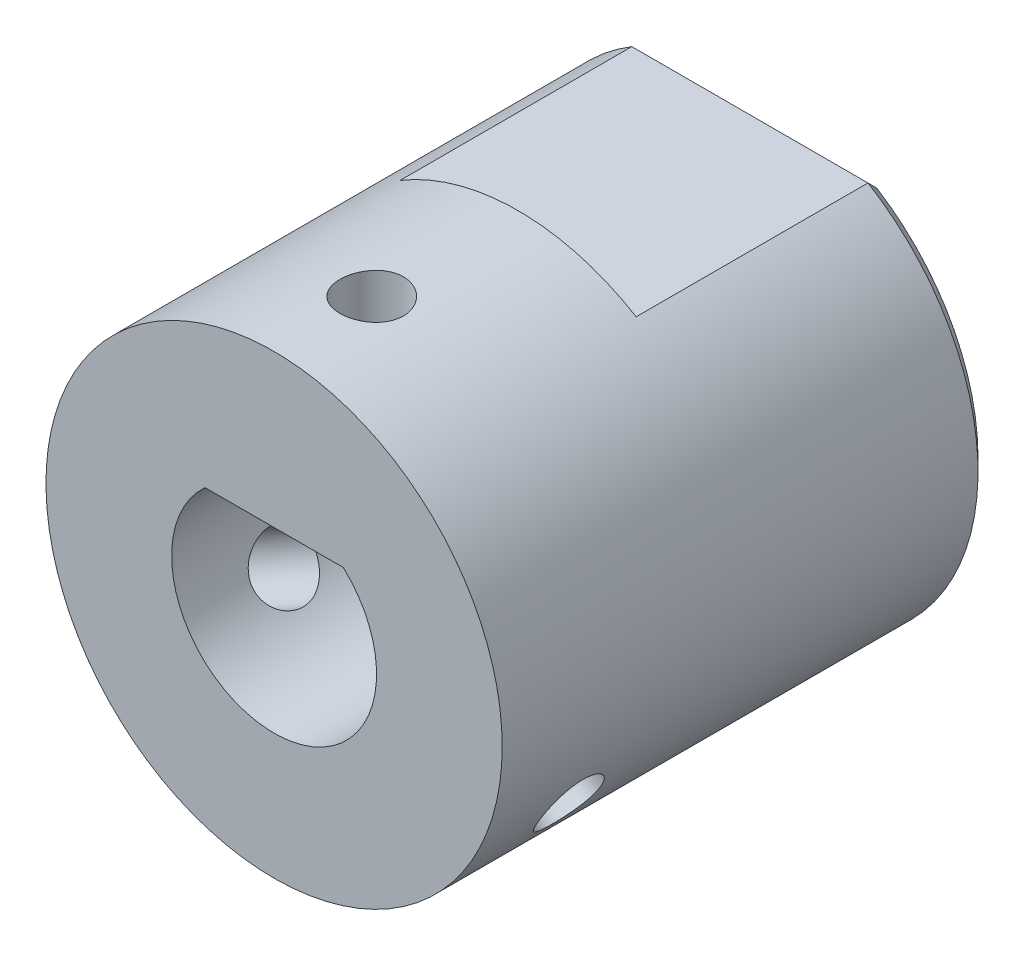
SolidWorks part; units mm, degrees
ref_plane "Спереди" through (0, 0, 0) normal (0, 0, 1) x (1, 0, 0)
ref_plane "Сверху" through (0, 0, 0) normal (0, 1, 0) x (1, 0, 0)
ref_plane "Справа" through (0, 0, 0) normal (1, 0, 0) x (0, 0, -1)
other "Configuration Table"
sketch "Эскиз2" plane through (0, 0, 0) normal (0, 0, 1) x (1, 0, 0)
  circle A0 centre (0, 0) radius 9.35
  circle A1 centre (0, 0) radius 4.2
  dimension "D1" = 18.7
  dimension "D2" = 8.4
extrude "Бобышка-Вытянуть1" add sketch "Эскиз2" along normal blind 20
ref_plane "Плоскость1" through (0, 9.35, 0) normal (0, 1, 0) x (1, 0, 0)
sketch "Эскиз4" plane through (0, 0, 20) normal (0, 0, 1) x (1, 0, 0)
  line L2 (-2.8337, 3.1) -> (2.8337, 3.1)
  arc A2 (-2.8337, 3.1) -> (2.8337, 3.1) centre (0, 0) cw
  circle A3 centre (0, 0) radius 4.2 construction
  point P3 (0, -4.1)
  point P6 (0, 0)
  point P9 (0, 0)
  dimension "D1" = 3.1
extrude "Бобышка-Вытянуть2" add sketch "Эскиз4" against normal blind 10
sketch "Эскиз3" plane through (0, 9.35, 0) normal (0, 1, 0) x (1, 0, 0)
  line L0 (-9.35, -20) -> (9.35, -20) construction
  circle A0 centre (0, -16) radius 1.3
  dimension "D2" = 2.6
  dimension "D1" = 4
extrude "Вырез-Вытянуть1" cut sketch "Эскиз3" against normal up to surface (5.15 mm away)
pattern_circular "Круговой массив1" count 3 over 360 about axis through (0, 0, 20) along (0, 0, -1) of "Вырез-Вытянуть1"
sketch "Эскиз5" plane through (0, 0, 0) normal (0, 0, -1) x (-1, 0, 0)
  line L0 (-4.8397, 8) -> (4.8397, 8)
  arc A0 (-4.8397, 8) -> (4.8397, 8) centre (0, 0) cw
  circle A1 centre (0, 0) radius 9.35 construction
  dimension "D1" = 8
extrude "Вырез-Вытянуть2" cut sketch "Эскиз5" against normal blind 10
chamfer "Фаска1" distance 0.5 angle 45 2 edges at (0, -9.35, 0) (0, 8, 0)
